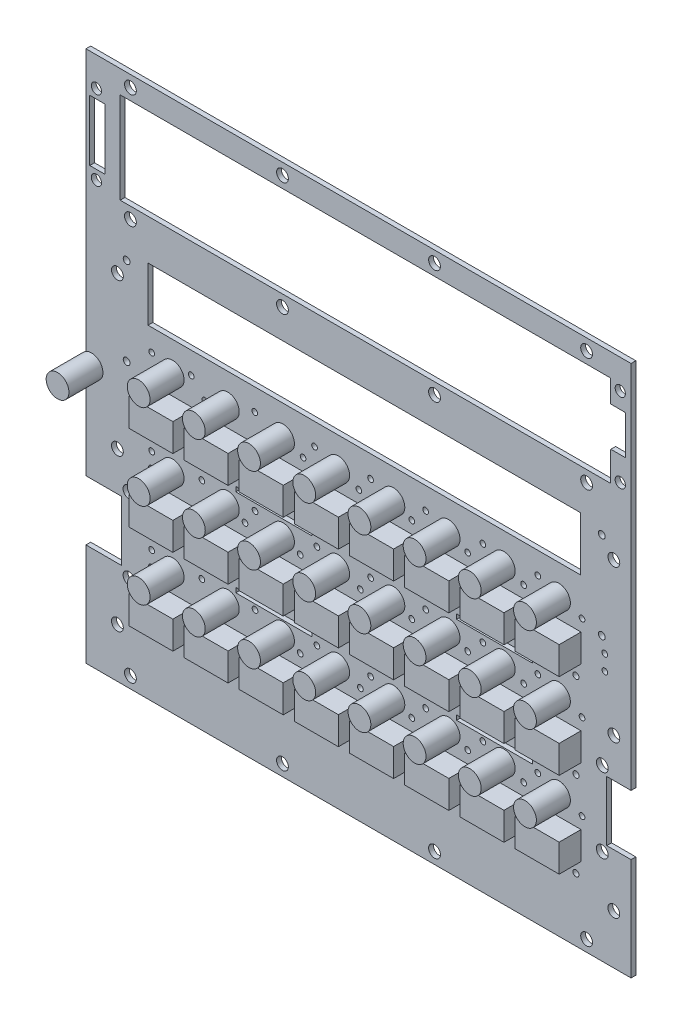
SolidWorks part; units mm, degrees
ref_plane "Front Plane" through (0, 0, 0) normal (0, 0, 1) x (1, 0, 0)
ref_plane "Top Plane" through (0, 0, 0) normal (0, 1, 0) x (1, 0, 0)
ref_plane "Right Plane" through (0, 0, 0) normal (1, 0, 0) x (0, 0, -1)
sketch "Sketch1" plane through (0, 0, 0) normal (0, 0, 1) x (1, 0, 0)
  line L0 (0, 0) -> (182.118, 0)
  line L1 (182.118, 0) -> (182.118, 34.2468)
  line L2 (182.118, 34.2468) -> (173.9875, 34.2468)
  line L3 (173.9875, 34.2468) -> (173.9875, 54.2468)
  line L4 (173.9875, 54.2468) -> (182.118, 54.2468)
  line L5 (182.118, 54.2468) -> (182.118, 177.8)
  line L6 (182.118, 177.8) -> (0, 177.8)
  line L7 (0, 177.8) -> (0, 54.2468)
  line L8 (0, 54.2468) -> (11.8694, 54.2468)
  line L9 (11.8694, 54.2468) -> (11.8694, 34.2468)
  line L10 (11.8694, 34.2468) -> (0, 34.2468)
  line L11 (0, 34.2468) -> (0, 0)
  line L12 (20.7391, 108.1786) -> (20.7391, 126.1796)
  line L13 (20.7391, 126.1796) -> (165.3007, 126.1796)
  line L14 (165.3007, 126.1796) -> (165.3007, 108.1786)
  line L15 (165.3007, 108.1786) -> (20.7391, 108.1786)
  line L16 (1.27, 144.653) -> (1.27, 164.973)
  line L17 (1.27, 164.973) -> (6.35, 164.973)
  line L18 (6.35, 164.973) -> (6.35, 144.653)
  line L19 (6.35, 144.653) -> (1.27, 144.653)
  line L20 (12.7, 170.18) -> (175.26, 170.18)
  line L21 (175.26, 170.18) -> (175.26, 162.6616)
  line L22 (175.26, 162.6616) -> (180.086, 162.6616)
  line L23 (180.086, 162.6616) -> (180.2892, 162.4584)
  line L24 (180.2892, 162.4584) -> (180.2892, 149.606)
  line L25 (180.2892, 149.606) -> (175.3616, 149.606)
  line L26 (175.3616, 149.606) -> (175.26, 149.5044)
  line L27 (175.26, 149.5044) -> (175.26, 139.7)
  line L28 (175.26, 139.7) -> (12.7, 139.7)
  line L29 (12.7, 139.7) -> (11.43, 139.7)
  line L30 (11.43, 139.7) -> (11.43, 170.18)
  line L31 (11.43, 170.18) -> (12.7, 170.18)
  line L32 (50.0634, 45.4152) -> (50.0634, 47.0027)
  line L33 (50.0634, 47.0027) -> (75.4634, 47.0027)
  line L34 (75.4634, 47.0027) -> (75.4634, 45.4152)
  line L35 (75.4634, 45.4152) -> (50.0634, 45.4152)
  line L36 (123.8134, 45.4152) -> (123.8134, 47.0027)
  line L37 (123.8134, 47.0027) -> (149.2134, 47.0027)
  line L38 (149.2134, 47.0027) -> (149.2134, 45.4152)
  line L39 (149.2134, 45.4152) -> (123.8134, 45.4152)
  line L40 (123.8134, 74.6252) -> (123.8134, 76.2127)
  line L41 (123.8134, 76.2127) -> (149.2134, 76.2127)
  line L42 (149.2134, 76.2127) -> (149.2134, 74.6252)
  line L43 (149.2134, 74.6252) -> (123.8134, 74.6252)
  line L44 (50.0634, 74.6252) -> (50.0634, 76.2127)
  line L45 (50.0634, 76.2127) -> (75.4634, 76.2127)
  line L46 (75.4634, 76.2127) -> (75.4634, 74.6252)
  line L47 (75.4634, 74.6252) -> (50.0634, 74.6252)
extrude "BOARD" add sketch "Sketch1" along normal blind 1.5921 separate body
ref_plane "Plane1" through (0, 0, 1.5921) normal (0, 0, 1) x (1, 0, 0)
sketch "Sketch2" plane through (0, 0, 1.5921) normal (0, 0, 1) x (1, 0, 0)
  circle A0 centre (1.8694, 86.9188) radius 3.81
extrude "LED-KINGBRIGHT_3P_2P54-1" add sketch "Sketch2" along normal blind 11.3538 separate body
sketch "Sketch3" plane through (0, 0, 1.5921) normal (0, 0, 1) x (1, 0, 0)
  circle A0 centre (158.0312, 41.1988) radius 3.81
extrude "LED-KINGBRIGHT_3P_2P54-2" add sketch "Sketch3" along normal blind 11.3538 separate body
sketch "Sketch4" plane through (0, 0, 1.5921) normal (0, 0, 1) x (1, 0, 0)
  circle A0 centre (139.5937, 41.1988) radius 3.81
extrude "LED-KINGBRIGHT_3P_2P54-3" add sketch "Sketch4" along normal blind 11.3538 separate body
sketch "Sketch5" plane through (0, 0, 1.5921) normal (0, 0, 1) x (1, 0, 0)
  circle A0 centre (121.1562, 41.1988) radius 3.81
extrude "LED-KINGBRIGHT_3P_2P54-4" add sketch "Sketch5" along normal blind 11.3538 separate body
sketch "Sketch6" plane through (0, 0, 1.5921) normal (0, 0, 1) x (1, 0, 0)
  circle A0 centre (102.7187, 41.1988) radius 3.81
extrude "LED-KINGBRIGHT_3P_2P54-5" add sketch "Sketch6" along normal blind 11.3538 separate body
sketch "Sketch7" plane through (0, 0, 1.5921) normal (0, 0, 1) x (1, 0, 0)
  circle A0 centre (158.0312, 69.7738) radius 3.81
extrude "LED-KINGBRIGHT_3P_2P54-6" add sketch "Sketch7" along normal blind 11.3538 separate body
sketch "Sketch8" plane through (0, 0, 1.5921) normal (0, 0, 1) x (1, 0, 0)
  circle A0 centre (139.5937, 69.7738) radius 3.81
extrude "LED-KINGBRIGHT_3P_2P54-7" add sketch "Sketch8" along normal blind 11.3538 separate body
sketch "Sketch9" plane through (0, 0, 1.5921) normal (0, 0, 1) x (1, 0, 0)
  circle A0 centre (121.1562, 69.7738) radius 3.81
extrude "LED-KINGBRIGHT_3P_2P54-8" add sketch "Sketch9" along normal blind 11.3538 separate body
sketch "Sketch10" plane through (0, 0, 1.5921) normal (0, 0, 1) x (1, 0, 0)
  circle A0 centre (102.7187, 69.7738) radius 3.81
extrude "LED-KINGBRIGHT_3P_2P54-9" add sketch "Sketch10" along normal blind 11.3538 separate body
sketch "Sketch11" plane through (0, 0, 1.5921) normal (0, 0, 1) x (1, 0, 0)
  circle A0 centre (84.2812, 41.1988) radius 3.81
extrude "LED-KINGBRIGHT_3P_2P54-10" add sketch "Sketch11" along normal blind 11.3538 separate body
sketch "Sketch12" plane through (0, 0, 1.5921) normal (0, 0, 1) x (1, 0, 0)
  circle A0 centre (65.8437, 41.1988) radius 3.81
extrude "LED-KINGBRIGHT_3P_2P54-11" add sketch "Sketch12" along normal blind 11.3538 separate body
sketch "Sketch13" plane through (0, 0, 1.5921) normal (0, 0, 1) x (1, 0, 0)
  circle A0 centre (47.4062, 41.1988) radius 3.81
extrude "LED-KINGBRIGHT_3P_2P54-12" add sketch "Sketch13" along normal blind 11.3538 separate body
sketch "Sketch14" plane through (0, 0, 1.5921) normal (0, 0, 1) x (1, 0, 0)
  circle A0 centre (28.9687, 41.1988) radius 3.81
extrude "LED-KINGBRIGHT_3P_2P54-13" add sketch "Sketch14" along normal blind 11.3538 separate body
sketch "Sketch15" plane through (0, 0, 1.5921) normal (0, 0, 1) x (1, 0, 0)
  circle A0 centre (84.2812, 69.7738) radius 3.81
extrude "LED-KINGBRIGHT_3P_2P54-14" add sketch "Sketch15" along normal blind 11.3538 separate body
sketch "Sketch16" plane through (0, 0, 1.5921) normal (0, 0, 1) x (1, 0, 0)
  circle A0 centre (65.8437, 69.7738) radius 3.81
extrude "LED-KINGBRIGHT_3P_2P54-15" add sketch "Sketch16" along normal blind 11.3538 separate body
sketch "Sketch17" plane through (0, 0, 1.5921) normal (0, 0, 1) x (1, 0, 0)
  circle A0 centre (47.4062, 69.7738) radius 3.81
extrude "LED-KINGBRIGHT_3P_2P54-16" add sketch "Sketch17" along normal blind 11.3538 separate body
sketch "Sketch18" plane through (0, 0, 1.5921) normal (0, 0, 1) x (1, 0, 0)
  circle A0 centre (28.9687, 69.7738) radius 3.81
extrude "LED-KINGBRIGHT_3P_2P54-17" add sketch "Sketch18" along normal blind 11.3538 separate body
sketch "Sketch19" plane through (0, 0, 1.5921) normal (0, 0, 1) x (1, 0, 0)
  circle A0 centre (158.0312, 98.3488) radius 3.81
extrude "LED-KINGBRIGHT_3P_2P54-18" add sketch "Sketch19" along normal blind 11.3538 separate body
sketch "Sketch20" plane through (0, 0, 1.5921) normal (0, 0, 1) x (1, 0, 0)
  circle A0 centre (139.5937, 98.3488) radius 3.81
extrude "LED-KINGBRIGHT_3P_2P54-19" add sketch "Sketch20" along normal blind 11.3538 separate body
sketch "Sketch21" plane through (0, 0, 1.5921) normal (0, 0, 1) x (1, 0, 0)
  circle A0 centre (121.1562, 98.3488) radius 3.81
extrude "LED-KINGBRIGHT_3P_2P54-20" add sketch "Sketch21" along normal blind 11.3538 separate body
sketch "Sketch22" plane through (0, 0, 1.5921) normal (0, 0, 1) x (1, 0, 0)
  circle A0 centre (102.7187, 98.3488) radius 3.81
extrude "LED-KINGBRIGHT_3P_2P54-21" add sketch "Sketch22" along normal blind 11.3538 separate body
sketch "Sketch23" plane through (0, 0, 1.5921) normal (0, 0, 1) x (1, 0, 0)
  circle A0 centre (84.2812, 98.3488) radius 3.81
extrude "LED-KINGBRIGHT_3P_2P54-22" add sketch "Sketch23" along normal blind 11.3538 separate body
sketch "Sketch24" plane through (0, 0, 1.5921) normal (0, 0, 1) x (1, 0, 0)
  circle A0 centre (65.8437, 98.3488) radius 3.81
extrude "LED-KINGBRIGHT_3P_2P54-23" add sketch "Sketch24" along normal blind 11.3538 separate body
sketch "Sketch25" plane through (0, 0, 1.5921) normal (0, 0, 1) x (1, 0, 0)
  circle A0 centre (47.4062, 98.3488) radius 3.81
extrude "LED-KINGBRIGHT_3P_2P54-24" add sketch "Sketch25" along normal blind 11.3538 separate body
sketch "Sketch26" plane through (0, 0, 1.5921) normal (0, 0, 1) x (1, 0, 0)
  circle A0 centre (28.9687, 98.3488) radius 3.81
extrude "LED-KINGBRIGHT_3P_2P54-25" add sketch "Sketch26" along normal blind 11.3538 separate body
sketch "Sketch27" plane through (0, 0, 1.5921) normal (0, 0, 1) x (1, 0, 0)
  line L0 (150.6652, 25.3238) -> (150.6652, 34.5948)
  line L1 (150.6652, 34.5948) -> (165.3972, 34.5948)
  line L2 (165.3972, 34.5948) -> (165.3972, 25.3238)
  line L3 (165.3972, 25.3238) -> (150.6652, 25.3238)
extrude "SWITCH-MCDTS2-1" add sketch "Sketch27" along normal blind 7.3 separate body
sketch "Sketch28" plane through (0, 0, 1.5921) normal (0, 0, 1) x (1, 0, 0)
  line L0 (150.6652, 53.8988) -> (150.6652, 63.1698)
  line L1 (150.6652, 63.1698) -> (165.3972, 63.1698)
  line L2 (165.3972, 63.1698) -> (165.3972, 53.8988)
  line L3 (165.3972, 53.8988) -> (150.6652, 53.8988)
extrude "SWITCH-MCDTS2-2" add sketch "Sketch28" along normal blind 7.3 separate body
sketch "Sketch29" plane through (0, 0, 1.5921) normal (0, 0, 1) x (1, 0, 0)
  line L0 (132.2277, 25.3238) -> (132.2277, 34.5948)
  line L1 (132.2277, 34.5948) -> (146.9597, 34.5948)
  line L2 (146.9597, 34.5948) -> (146.9597, 25.3238)
  line L3 (146.9597, 25.3238) -> (132.2277, 25.3238)
extrude "SWITCH-MCDTS2-3" add sketch "Sketch29" along normal blind 7.3 separate body
sketch "Sketch30" plane through (0, 0, 1.5921) normal (0, 0, 1) x (1, 0, 0)
  line L0 (113.7902, 25.3238) -> (113.7902, 34.5948)
  line L1 (113.7902, 34.5948) -> (128.5222, 34.5948)
  line L2 (128.5222, 34.5948) -> (128.5222, 25.3238)
  line L3 (128.5222, 25.3238) -> (113.7902, 25.3238)
extrude "SWITCH-MCDTS2-4" add sketch "Sketch30" along normal blind 7.3 separate body
sketch "Sketch31" plane through (0, 0, 1.5921) normal (0, 0, 1) x (1, 0, 0)
  line L0 (95.3527, 25.3238) -> (95.3527, 34.5948)
  line L1 (95.3527, 34.5948) -> (110.0847, 34.5948)
  line L2 (110.0847, 34.5948) -> (110.0847, 25.3238)
  line L3 (110.0847, 25.3238) -> (95.3527, 25.3238)
extrude "SWITCH-MCDTS2-5" add sketch "Sketch31" along normal blind 7.3 separate body
sketch "Sketch32" plane through (0, 0, 1.5921) normal (0, 0, 1) x (1, 0, 0)
  line L0 (76.9152, 25.3238) -> (76.9152, 34.5948)
  line L1 (76.9152, 34.5948) -> (91.6472, 34.5948)
  line L2 (91.6472, 34.5948) -> (91.6472, 25.3238)
  line L3 (91.6472, 25.3238) -> (76.9152, 25.3238)
extrude "SWITCH-MCDTS2-6" add sketch "Sketch32" along normal blind 7.3 separate body
sketch "Sketch33" plane through (0, 0, 1.5921) normal (0, 0, 1) x (1, 0, 0)
  line L0 (58.4777, 25.3238) -> (58.4777, 34.5948)
  line L1 (58.4777, 34.5948) -> (73.2097, 34.5948)
  line L2 (73.2097, 34.5948) -> (73.2097, 25.3238)
  line L3 (73.2097, 25.3238) -> (58.4777, 25.3238)
extrude "SWITCH-MCDTS2-7" add sketch "Sketch33" along normal blind 7.3 separate body
sketch "Sketch34" plane through (0, 0, 1.5921) normal (0, 0, 1) x (1, 0, 0)
  line L0 (40.0402, 25.3238) -> (40.0402, 34.5948)
  line L1 (40.0402, 34.5948) -> (54.7722, 34.5948)
  line L2 (54.7722, 34.5948) -> (54.7722, 25.3238)
  line L3 (54.7722, 25.3238) -> (40.0402, 25.3238)
extrude "SWITCH-MCDTS2-8" add sketch "Sketch34" along normal blind 7.3 separate body
sketch "Sketch35" plane through (0, 0, 1.5921) normal (0, 0, 1) x (1, 0, 0)
  line L0 (21.6027, 25.3238) -> (21.6027, 34.5948)
  line L1 (21.6027, 34.5948) -> (36.3347, 34.5948)
  line L2 (36.3347, 34.5948) -> (36.3347, 25.3238)
  line L3 (36.3347, 25.3238) -> (21.6027, 25.3238)
extrude "SWITCH-MCDTS2-9" add sketch "Sketch35" along normal blind 7.3 separate body
sketch "Sketch36" plane through (0, 0, 1.5921) normal (0, 0, 1) x (1, 0, 0)
  line L0 (132.2277, 53.8988) -> (132.2277, 63.1698)
  line L1 (132.2277, 63.1698) -> (146.9597, 63.1698)
  line L2 (146.9597, 63.1698) -> (146.9597, 53.8988)
  line L3 (146.9597, 53.8988) -> (132.2277, 53.8988)
extrude "SWITCH-MCDTS2-10" add sketch "Sketch36" along normal blind 7.3 separate body
sketch "Sketch37" plane through (0, 0, 1.5921) normal (0, 0, 1) x (1, 0, 0)
  line L0 (113.7902, 53.8988) -> (113.7902, 63.1698)
  line L1 (113.7902, 63.1698) -> (128.5222, 63.1698)
  line L2 (128.5222, 63.1698) -> (128.5222, 53.8988)
  line L3 (128.5222, 53.8988) -> (113.7902, 53.8988)
extrude "SWITCH-MCDTS2-11" add sketch "Sketch37" along normal blind 7.3 separate body
sketch "Sketch38" plane through (0, 0, 1.5921) normal (0, 0, 1) x (1, 0, 0)
  line L0 (95.3527, 53.8988) -> (95.3527, 63.1698)
  line L1 (95.3527, 63.1698) -> (110.0847, 63.1698)
  line L2 (110.0847, 63.1698) -> (110.0847, 53.8988)
  line L3 (110.0847, 53.8988) -> (95.3527, 53.8988)
extrude "SWITCH-MCDTS2-12" add sketch "Sketch38" along normal blind 7.3 separate body
sketch "Sketch39" plane through (0, 0, 1.5921) normal (0, 0, 1) x (1, 0, 0)
  line L0 (76.9152, 53.8988) -> (76.9152, 63.1698)
  line L1 (76.9152, 63.1698) -> (91.6472, 63.1698)
  line L2 (91.6472, 63.1698) -> (91.6472, 53.8988)
  line L3 (91.6472, 53.8988) -> (76.9152, 53.8988)
extrude "SWITCH-MCDTS2-13" add sketch "Sketch39" along normal blind 7.3 separate body
sketch "Sketch40" plane through (0, 0, 1.5921) normal (0, 0, 1) x (1, 0, 0)
  line L0 (58.4777, 53.8988) -> (58.4777, 63.1698)
  line L1 (58.4777, 63.1698) -> (73.2097, 63.1698)
  line L2 (73.2097, 63.1698) -> (73.2097, 53.8988)
  line L3 (73.2097, 53.8988) -> (58.4777, 53.8988)
extrude "SWITCH-MCDTS2-14" add sketch "Sketch40" along normal blind 7.3 separate body
sketch "Sketch41" plane through (0, 0, 1.5921) normal (0, 0, 1) x (1, 0, 0)
  line L0 (40.0402, 53.8988) -> (40.0402, 63.1698)
  line L1 (40.0402, 63.1698) -> (54.7722, 63.1698)
  line L2 (54.7722, 63.1698) -> (54.7722, 53.8988)
  line L3 (54.7722, 53.8988) -> (40.0402, 53.8988)
extrude "SWITCH-MCDTS2-15" add sketch "Sketch41" along normal blind 7.3 separate body
sketch "Sketch42" plane through (0, 0, 1.5921) normal (0, 0, 1) x (1, 0, 0)
  line L0 (21.6027, 53.8988) -> (21.6027, 63.1698)
  line L1 (21.6027, 63.1698) -> (36.3347, 63.1698)
  line L2 (36.3347, 63.1698) -> (36.3347, 53.8988)
  line L3 (36.3347, 53.8988) -> (21.6027, 53.8988)
extrude "SWITCH-MCDTS2-16" add sketch "Sketch42" along normal blind 7.3 separate body
sketch "Sketch43" plane through (0, 0, 1.5921) normal (0, 0, 1) x (1, 0, 0)
  line L0 (150.6652, 82.4738) -> (150.6652, 91.7448)
  line L1 (150.6652, 91.7448) -> (165.3972, 91.7448)
  line L2 (165.3972, 91.7448) -> (165.3972, 82.4738)
  line L3 (165.3972, 82.4738) -> (150.6652, 82.4738)
extrude "SWITCH-MCDTS2-17" add sketch "Sketch43" along normal blind 7.3 separate body
sketch "Sketch44" plane through (0, 0, 1.5921) normal (0, 0, 1) x (1, 0, 0)
  line L0 (132.2277, 82.4738) -> (132.2277, 91.7448)
  line L1 (132.2277, 91.7448) -> (146.9597, 91.7448)
  line L2 (146.9597, 91.7448) -> (146.9597, 82.4738)
  line L3 (146.9597, 82.4738) -> (132.2277, 82.4738)
extrude "SWITCH-MCDTS2-18" add sketch "Sketch44" along normal blind 7.3 separate body
sketch "Sketch45" plane through (0, 0, 1.5921) normal (0, 0, 1) x (1, 0, 0)
  line L0 (113.7902, 82.4738) -> (113.7902, 91.7448)
  line L1 (113.7902, 91.7448) -> (128.5222, 91.7448)
  line L2 (128.5222, 91.7448) -> (128.5222, 82.4738)
  line L3 (128.5222, 82.4738) -> (113.7902, 82.4738)
extrude "SWITCH-MCDTS2-19" add sketch "Sketch45" along normal blind 7.3 separate body
sketch "Sketch46" plane through (0, 0, 1.5921) normal (0, 0, 1) x (1, 0, 0)
  line L0 (95.3527, 82.4738) -> (95.3527, 91.7448)
  line L1 (95.3527, 91.7448) -> (110.0847, 91.7448)
  line L2 (110.0847, 91.7448) -> (110.0847, 82.4738)
  line L3 (110.0847, 82.4738) -> (95.3527, 82.4738)
extrude "SWITCH-MCDTS2-20" add sketch "Sketch46" along normal blind 7.3 separate body
sketch "Sketch47" plane through (0, 0, 1.5921) normal (0, 0, 1) x (1, 0, 0)
  line L0 (76.9152, 82.4738) -> (76.9152, 91.7448)
  line L1 (76.9152, 91.7448) -> (91.6472, 91.7448)
  line L2 (91.6472, 91.7448) -> (91.6472, 82.4738)
  line L3 (91.6472, 82.4738) -> (76.9152, 82.4738)
extrude "SWITCH-MCDTS2-21" add sketch "Sketch47" along normal blind 7.3 separate body
sketch "Sketch48" plane through (0, 0, 1.5921) normal (0, 0, 1) x (1, 0, 0)
  line L0 (58.4777, 82.4738) -> (58.4777, 91.7448)
  line L1 (58.4777, 91.7448) -> (73.2097, 91.7448)
  line L2 (73.2097, 91.7448) -> (73.2097, 82.4738)
  line L3 (73.2097, 82.4738) -> (58.4777, 82.4738)
extrude "SWITCH-MCDTS2-22" add sketch "Sketch48" along normal blind 7.3 separate body
sketch "Sketch49" plane through (0, 0, 1.5921) normal (0, 0, 1) x (1, 0, 0)
  line L0 (40.0402, 82.4738) -> (40.0402, 91.7448)
  line L1 (40.0402, 91.7448) -> (54.7722, 91.7448)
  line L2 (54.7722, 91.7448) -> (54.7722, 82.4738)
  line L3 (54.7722, 82.4738) -> (40.0402, 82.4738)
extrude "SWITCH-MCDTS2-23" add sketch "Sketch49" along normal blind 7.3 separate body
sketch "Sketch50" plane through (0, 0, 1.5921) normal (0, 0, 1) x (1, 0, 0)
  line L0 (21.6027, 82.4738) -> (21.6027, 91.7448)
  line L1 (21.6027, 91.7448) -> (36.3347, 91.7448)
  line L2 (36.3347, 91.7448) -> (36.3347, 82.4738)
  line L3 (36.3347, 82.4738) -> (21.6027, 82.4738)
extrude "SWITCH-MCDTS2-24" add sketch "Sketch50" along normal blind 7.3 separate body
sketch "Sketch56" plane through (0, 0, 1.5921) normal (0, 0, 1) x (1, 0, 0)
  circle B0 centre (163.703, 21.1074) radius 1.016
  circle B1 centre (163.703, 49.6824) radius 1.016
  circle B2 centre (145.2626, 21.8186) radius 0.9652
  circle B3 centre (126.8476, 21.6154) radius 0.9652
  circle B4 centre (108.4072, 21.7424) radius 0.9652
  circle B5 centre (89.9668, 21.844) radius 0.9652
  circle B6 centre (71.5264, 20.7772) radius 0.9652
  circle B7 centre (53.086, 21.1582) radius 0.9652
  circle B8 centre (34.6472, 21.1328) radius 1.016
  circle B9 centre (145.2626, 49.5554) radius 1.016
  circle B10 centre (126.8222, 49.3522) radius 1.016
  circle B11 centre (108.3818, 49.1236) radius 1.016
  circle B12 centre (89.9414, 49.6824) radius 1.016
  circle B13 centre (71.501, 49.1998) radius 1.016
  circle B14 centre (53.0606, 49.1998) radius 1.016
  circle B15 centre (34.6202, 49.276) radius 1.016
  circle B16 centre (163.703, 78.2574) radius 1.016
  circle B17 centre (145.2626, 77.7748) radius 1.016
  circle B18 centre (126.746, 78.3336) radius 1.016
  circle B19 centre (108.3818, 78.74) radius 1.016
  circle B20 centre (89.9414, 78.3336) radius 1.016
  circle B21 centre (71.501, 78.2574) radius 1.016
  circle B22 centre (53.0606, 78.4098) radius 1.016
  circle B23 centre (34.6202, 78.0542) radius 1.016
  circle B24 centre (91.694, 38.6588) radius 0.9525
  circle B25 centre (77.1652, 43.7388) radius 0.9525
  circle B26 centre (71.5772, 38.6588) radius 0.9525
  circle B27 centre (56.4896, 43.7388) radius 0.9525
  circle B28 centre (38.735, 43.7388) radius 0.9525
  circle B29 centre (21.8948, 38.6588) radius 0.9525
  circle B30 centre (21.971, 43.7388) radius 0.9525
  circle B31 centre (77.1652, 72.3138) radius 0.9525
  circle B32 centre (91.694, 67.2338) radius 0.9525
  circle B33 centre (71.5772, 67.2338) radius 0.9525
  circle B34 centre (56.4896, 72.3138) radius 0.9525
  circle B35 centre (53.1368, 67.2338) radius 0.9525
  circle B36 centre (38.735, 72.3138) radius 0.9525
  circle B37 centre (21.8948, 67.2338) radius 0.9525
  circle B38 centre (21.971, 72.3138) radius 0.9525
  circle B39 centre (165.735, 95.8088) radius 0.9525
  circle B40 centre (150.9776, 100.8888) radius 0.9525
  circle B41 centre (146.2278, 95.8088) radius 0.9525
  circle B42 centre (132.6134, 100.8888) radius 0.9525
  circle B43 centre (113.4872, 100.8888) radius 0.9525
  circle B44 centre (127.508, 95.8088) radius 0.9525
  circle B45 centre (108.8644, 95.8088) radius 0.9525
  circle B46 centre (95.0976, 100.8888) radius 0.9525
  circle B47 centre (91.186, 95.8088) radius 0.9525
  circle B48 centre (76.3778, 100.8888) radius 0.9525
  circle B49 centre (72.5424, 95.8088) radius 0.9525
  circle B50 centre (56.4134, 100.8888) radius 0.9525
  circle B51 centre (39.7256, 95.8088) radius 0.9525
  circle B52 centre (35.179, 100.8888) radius 0.9525
  circle B53 centre (24.2062, 95.8088) radius 0.9525
  circle B54 centre (21.971, 100.8888) radius 0.9525
  circle B55 centre (132.6134, 72.3138) radius 0.9525
  circle B56 centre (146.2278, 67.2338) radius 0.9525
  circle B57 centre (113.4872, 72.3138) radius 0.9525
  circle B58 centre (127.508, 67.2338) radius 0.9525
  circle B59 centre (95.0976, 72.3138) radius 0.9525
  circle B60 centre (108.8644, 67.2338) radius 0.9525
  circle B61 centre (150.9776, 43.7388) radius 0.9525
  circle B62 centre (132.6134, 43.7388) radius 0.9525
  circle B63 centre (113.4872, 43.7388) radius 0.9525
  circle B64 centre (95.0976, 43.7388) radius 0.9525
  circle B65 centre (108.8644, 38.6588) radius 0.9525
  circle B66 centre (150.9776, 72.3138) radius 0.9525
  circle B67 centre (165.735, 67.2338) radius 0.9525
  circle B68 centre (173.3296, 89.4588) radius 0.9525
  circle B69 centre (173.355, 84.3534) radius 0.9525
  circle B70 centre (176.3725, 118.11) radius 1.9685
  circle B71 centre (176.3725, 67.31) radius 1.9685
  circle B72 centre (176.3725, 16.51) radius 1.9685
  circle B73 centre (167.259, 135.89) radius 1.9685
  circle B74 centre (116.459, 135.89) radius 1.9685
  circle B75 centre (65.659, 135.89) radius 1.9685
  circle B76 centre (14.859, 135.89) radius 1.9685
  circle B77 centre (10.5105, 118.11) radius 1.9685
  circle B78 centre (10.5105, 67.31) radius 1.9685
  circle B79 centre (10.5105, 16.51) radius 1.9685
  circle B80 centre (165.735, 38.6588) radius 0.9525
  circle B81 centre (146.2278, 38.6588) radius 0.9525
  circle B82 centre (127.508, 38.6588) radius 0.9525
  circle B83 centre (14.859, 173.99) radius 1.9685
  circle B84 centre (65.659, 173.99) radius 1.9685
  circle B85 centre (116.459, 173.99) radius 1.9685
  circle B86 centre (167.259, 173.99) radius 1.9685
  circle B87 centre (167.259, 3.81) radius 1.9685
  circle B88 centre (116.459, 3.81) radius 1.9685
  circle B89 centre (65.659, 3.81) radius 1.9685
  circle B90 centre (14.859, 3.81) radius 1.9685
  circle B91 centre (172.5066, 56.7436) radius 1.9685
  circle B92 centre (172.5066, 31.75) radius 1.9685
  circle B93 centre (14.3688, 56.7436) radius 1.9685
  circle B94 centre (14.3688, 31.75) radius 1.9685
  circle B95 centre (172.3415, 123.3754) radius 1.1303
  circle B96 centre (172.3415, 94.1654) radius 1.1303
  circle B97 centre (13.5915, 94.1654) radius 1.1303
  circle B98 centre (13.5915, 123.3754) radius 1.1303
  circle B99 centre (178.5137, 141.5618) radius 1.7145
  circle B100 centre (178.5137, 168.0616) radius 1.7145
  circle B101 centre (3.5001, 168.0616) radius 1.7145
  circle B102 centre (3.5001, 141.5618) radius 1.7145
sketch_block_instance "Block-Model-1"
sketch_block "Block-Model"
extrude "Cut-Extrude1" cut sketch "Sketch56" against normal blind 10
